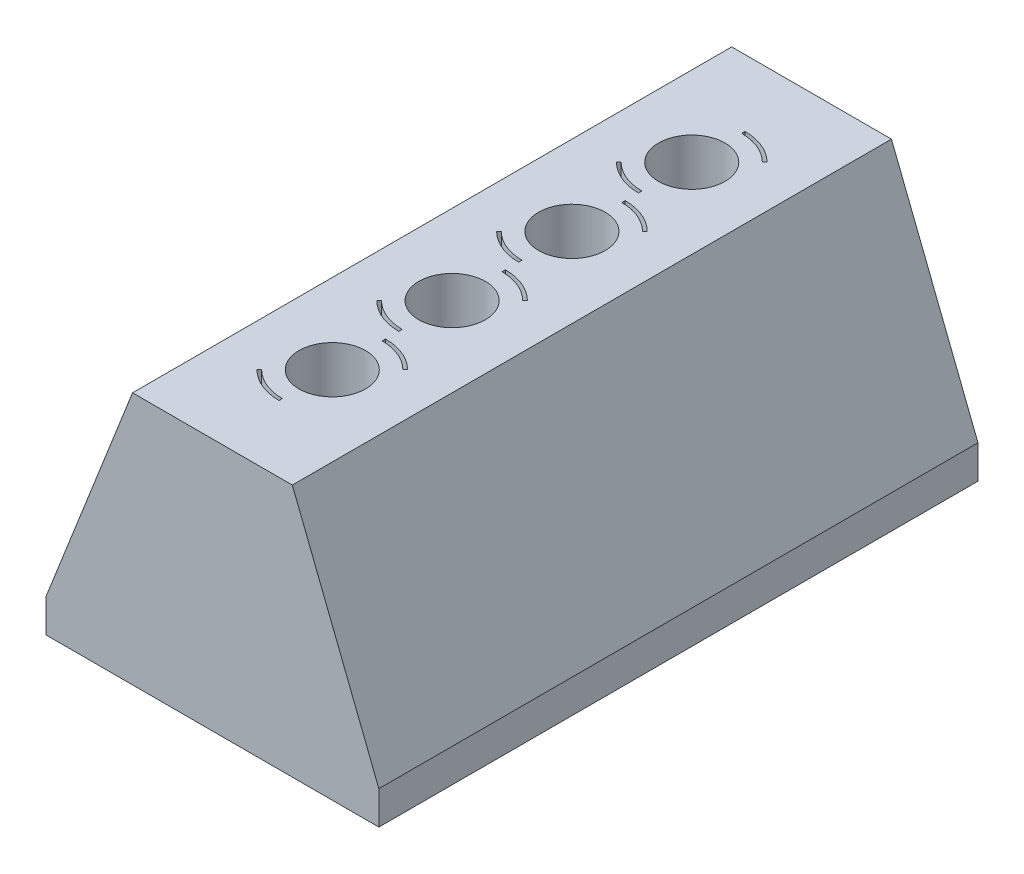
SolidWorks part; units mm, degrees
ref_plane "Piano frontale" through (0, 0, 0) normal (0, 0, 1) x (1, 0, 0)
ref_plane "Piano superiore" through (0, 0, 0) normal (0, 1, 0) x (1, 0, 0)
ref_plane "Piano destro" through (0, 0, 0) normal (1, 0, 0) x (0, 0, -1)
sketch "Schizzo1" plane through (0, 0, 0) normal (0, 0, 1) x (1, 0, 0)
  line L0 (-125, 0) -> (125, 0)
  line L2 (60, 190) -> (-60, 190)
  line L4 (-125, 0) -> (-125, 25)
  line L5 (-125, 25) -> (-60, 190)
  line L6 (125, 0) -> (125, 25)
  line L7 (125, 25) -> (60, 190)
  point P2 (0, 190)
  point P4 (0, 0)
  point P5 (0, 0)
  dimension "D1" = 190
  dimension "D2" = 120
  dimension "D3" = 250
  dimension "D4" = 25
extrude "Estrusione-Estrusione1" add sketch "Schizzo1" along normal mid plane 450
sketch "Schizzo2" plane through (0, 190, 0) normal (0, 1, 0) x (1, 0, 0)
  line L0 (0, -225) -> (0, -135)
  line L1 (60, -225) -> (-60, -225) construction
  line L2 (0, -135) -> (0, -45)
  line L3 (0, -45) -> (0, 45)
  line L4 (0, 45) -> (0, 135)
  line L5 (0, 135) -> (0, 225)
  line L6 (60, 225) -> (-60, 225) construction
  circle A0 centre (0, -135) radius 25
  circle A1 centre (0, -45) radius 25
  circle A2 centre (0, 45) radius 25
  circle A3 centre (0, 135) radius 25
  point P0 (0, 0)
  point P13 (0, 0)
  dimension "D1" = 50
extrude "Taglio-Estrusione1" cut sketch "Schizzo2" against normal blind 90 contours L0 A0 L2 | L2 A0 L0 | L2 A1 L3 | L3 A1 L2 | L3 A2 L4 | L4 A2 L3 | L4 A3 L5 | L5 A3 L4
shell "Svuota1" thickness 15
sketch "Schizzo4" plane through (0, 85, 0) normal (0, -1, 0) x (1, 0, 0)
  circle A0 centre (0, -135) radius 40 construction
  circle A1 centre (0, -45) radius 40 construction
  circle A2 centre (0, 45) radius 40 construction
  circle A3 centre (0, 135) radius 40 construction
  circle A4 centre (0, -135) radius 40
  circle A5 centre (0, -45) radius 40
  circle A6 centre (0, 45) radius 40
  circle A7 centre (0, 135) radius 40
extrude "Taglio-Estrusione2" cut sketch "Schizzo4" against normal blind 20 contours A6 | A5 | A4
ref_plane "Piano1" through (0, 105, 0) normal (0, 1, 0) x (1, 0, 0)
sketch "Schizzo6" plane through (0, 105, 0) normal (0, 1, 0) x (1, 0, 0)
  line L0 (-77.3629, 210) -> (-77.3629, -225)
  line L1 (-77.3629, 210) -> (-77.3629, -225)
  line L2 (77.3629, -225) -> (77.3629, 210)
  line L3 (77.3629, -225) -> (77.3629, 210)
  line L4 (-77.3629, -225) -> (77.3629, -225)
  line L5 (-77.3629, 210) -> (77.3629, 210)
  circle A0 centre (0, 135) radius 40 construction
  circle A1 centre (0, 45) radius 40 construction
  circle A2 centre (0, -45) radius 40 construction
  circle A3 centre (0, -135) radius 40 construction
  circle A4 centre (0, 135) radius 40
  circle A5 centre (0, 45) radius 40
  circle A6 centre (0, -45) radius 40
  circle A7 centre (0, -135) radius 40
extrude "Estrusione-Estrusione2" add sketch "Schizzo6" along normal blind 10
sketch "Schizzo7" plane through (0, 0, 225) normal (0, 0, 1) x (1, 0, 0)
  line L6 (-125, 25) -> (-125, 0)
  line L7 (-125, 0) -> (125, 0)
  line L8 (125, 0) -> (125, 25)
  line L9 (125, 25) -> (60, 190)
  line L10 (60, 190) -> (-60, 190)
  line L11 (-60, 190) -> (-125, 25)
  line L12 (-125, 25) -> (-125, 0)
  line L13 (-125, 0) -> (125, 0)
  line L14 (125, 0) -> (125, 25)
  line L15 (125, 25) -> (60, 190)
  line L16 (60, 190) -> (-60, 190)
  line L17 (-60, 190) -> (-125, 25)
  dimension "D1" = 0
extrude "Estrusione-Estrusione3" add sketch "Schizzo7" against normal blind 15
sketch "Schizzo12" plane through (0, 0, -210) normal (0, 0, 1) x (1, 0, 0)
  line L0 (0, 105) -> (0, 15)
  line L1 (77.3629, 105) -> (-77.3629, 105) construction
  line L2 (-110, 15) -> (110, 15) construction
  circle A0 centre (0, 60) radius 35
  dimension "D1" = 70
extrude "Taglio-Estrusione12" cut sketch "Schizzo12" against normal through all contours L0 A0 | L0 A0
sketch "Schizzo13" plane through (0, 190, 0) normal (0, 1, 0) x (1, 0, 0)
  line L0 (0, 97.5) -> (0, 95)
  line L1 (-26.5165, 108.4835) -> (-28.2843, 106.7157)
  line L2 (26.5165, 161.5165) -> (28.2843, 163.2843)
  line L3 (0, 172.5) -> (0, 175)
  line L4 (-26.5165, 18.4835) -> (-28.2843, 16.7157)
  line L5 (0, 7.5) -> (0, 5)
  line L6 (26.5165, 71.5165) -> (28.2843, 73.2843)
  line L7 (0, 82.5) -> (0, 85)
  line L8 (-26.5165, -71.5165) -> (-28.2843, -73.2843)
  line L9 (0, -82.5) -> (0, -85)
  line L10 (26.5165, -18.4835) -> (28.2843, -16.7157)
  line L11 (0, -7.5) -> (0, -5)
  line L12 (-26.5165, -161.5165) -> (-28.2843, -163.2843)
  line L13 (0, -172.5) -> (0, -175)
  line L14 (26.5165, -108.4835) -> (28.2843, -106.7157)
  line L15 (0, -97.5) -> (0, -95)
  arc A0 (-26.5165, 108.4835) -> (0, 97.5) centre (0, 135) ccw
  arc A1 (-28.2843, 106.7157) -> (0, 95) centre (0, 135) ccw
  arc A2 (26.5165, 161.5165) -> (0, 172.5) centre (0, 135) ccw
  arc A3 (28.2843, 163.2843) -> (0, 175) centre (0, 135) ccw
  arc A4 (-26.5165, 18.4835) -> (0, 7.5) centre (0, 45) ccw
  arc A5 (-28.2843, 16.7157) -> (0, 5) centre (0, 45) ccw
  arc A6 (26.5165, 71.5165) -> (0, 82.5) centre (0, 45) ccw
  arc A7 (28.2843, 73.2843) -> (0, 85) centre (0, 45) ccw
  arc A8 (-26.5165, -71.5165) -> (0, -82.5) centre (0, -45) ccw
  arc A9 (-28.2843, -73.2843) -> (0, -85) centre (0, -45) ccw
  arc A10 (26.5165, -18.4835) -> (0, -7.5) centre (0, -45) ccw
  arc A11 (28.2843, -16.7157) -> (0, -5) centre (0, -45) ccw
  arc A12 (-26.5165, -161.5165) -> (0, -172.5) centre (0, -135) ccw
  arc A13 (-28.2843, -163.2843) -> (0, -175) centre (0, -135) ccw
  arc A14 (26.5165, -108.4835) -> (0, -97.5) centre (0, -135) ccw
  arc A15 (28.2843, -106.7157) -> (0, -95) centre (0, -135) ccw
  dimension "D1" = 75
  dimension "D2" = 80
  dimension "D3" = 45
  dimension "D5" = 4
  dimension "D4" = 2
extrude "Taglio-Estrusione13" cut sketch "Schizzo13" against normal blind 20
